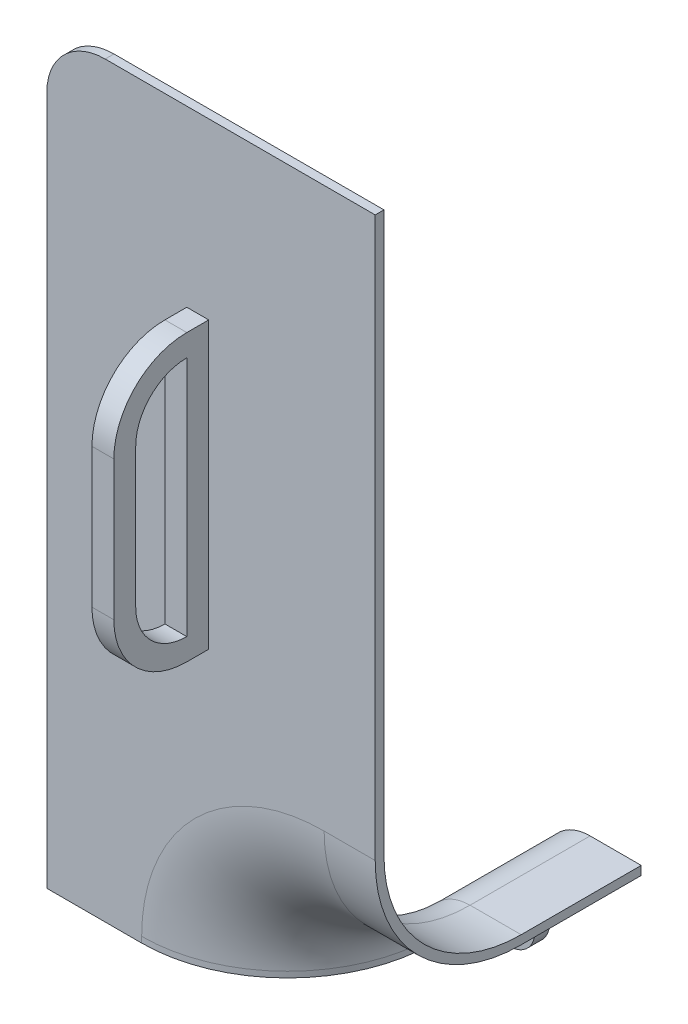
SolidWorks part; units mm, degrees
ref_plane "Front Plane" through (0, 0, 0) normal (0, 0, 1) x (1, 0, 0)
ref_plane "Top Plane" through (0, 0, 0) normal (0, 1, 0) x (1, 0, 0)
ref_plane "Right Plane" through (0, 0, 0) normal (1, 0, 0) x (0, 0, -1)
sketch "Sketch1" plane through (0, 0, 0) normal (0, 0, 1) x (1, 0, 0)
  line L0 (-72.7315, -496.2154) -> (-35.7315, -496.2154)
  line L2 (-35.7315, -496.2154) -> (-35.7315, -592.8312)
  line L3 (-47.7315, -598.6272) -> (-80.7315, -598.6272)
  line L4 (-80.7315, -598.6272) -> (-80.7315, -504.2154)
  line L5 (-50.7315, -599.6272) -> (-52.7315, -599.6272) construction
  line L7 (-0.7315, -587.8312) -> (-52.7315, -587.8312) construction
  line L10 (-35.7315, -592.8312) -> (-47.7315, -592.8312)
  line L11 (-47.7315, -598.6272) -> (-47.7315, -592.8312)
  line L16 (-52.7315, -714.7029) -> (-52.7315, -587.6272) construction
  arc A1 (-72.7315, -496.2154) -> (-80.7315, -504.2154) centre (-72.7315, -504.2154) ccw
  point P18 (0, 0)
  dimension "D1" = 1
  dimension "D2" = 45
  dimension "D3" = 5
  dimension "D4" = 5
extrude "Boss-Extrude1" add sketch "Sketch1" along normal offset from surface (36.45 mm away) 3
fillet "Fillet1" radius 5 1 edges at (-47.7315, -592.8312, 18.225)
fillet "Fillet2" radius 20 3 edges at (-47.7315, -598.2292, 36.45) (-39.2315, -592.8312, 36.45) (-46.267, -594.2956, 36.45)
shell "Shell2" thickness 1.2
sketch "Sketch3" plane through (0, 0, 8) normal (0, 0, 1) x (1, 0, 0)
  line L4 (-47.7315, -597.8312) -> (-47.7315, -600.2705)
  line L5 (-47.7315, -600.2705) -> (-43.7922, -600.2705)
  line L6 (-40.2922, -596.7705) -> (-40.2922, -592.8312)
  line L7 (-40.2922, -592.8312) -> (-42.7315, -592.8312)
  line L8 (-47.7315, -597.8312) -> (-47.7315, -600.2705)
  line L9 (-47.7315, -600.2705) -> (-43.7922, -600.2705)
  line L10 (-40.2922, -596.7705) -> (-40.2922, -592.8312)
  line L11 (-40.2922, -592.8312) -> (-42.7315, -592.8312)
  circle A1 centre (-43.7922, -596.7705) radius 1.5
  arc A2 (-42.7315, -592.8312) -> (-47.7315, -597.8312) centre (-42.7315, -597.8312) ccw
  arc A3 (-43.7922, -600.2705) -> (-40.2922, -596.7705) centre (-43.7922, -596.7705) ccw
  arc A4 (-42.7315, -592.8312) -> (-47.7315, -597.8312) centre (-42.7315, -597.8312) ccw
  arc A5 (-43.7922, -600.2705) -> (-40.2922, -596.7705) centre (-43.7922, -596.7705) ccw
  dimension "D1" = 0
extrude "Boss-Extrude2" add sketch "Sketch3" along normal blind 2
sketch "Sketch4" plane through (0, 0, 36.45) normal (0, 0, 1) x (1, 0, 0)
  line L1 (-61.5453, -520.0813) -> (-58.5453, -520.0813)
  line L2 (-61.5453, -520.0813) -> (-61.5453, -559.1646)
  line L3 (-61.5453, -559.1646) -> (-58.5453, -559.1646)
  line L4 (-58.5453, -520.0813) -> (-58.5453, -559.1646)
  dimension "D1" = 3
extrude "Boss-Extrude3" add sketch "Sketch4" along normal blind 13
fillet "Fillet3" radius 10 2 edges at (-60.0453, -559.1646, 49.45) (-60.0453, -520.0813, 49.45)
sketch "Sketch5" plane through (-58.5453, 0, 0) normal (1, 0, 0) x (0, 0, -1)
  line L4 (-49.45, -530.0813) -> (-49.45, -549.1646)
  line L5 (-39.45, -559.1646) -> (-36.45, -559.1646)
  line L6 (-36.45, -559.1646) -> (-36.45, -520.0813)
  line L7 (-36.45, -520.0813) -> (-39.45, -520.0813)
  line L8 (-49.45, -530.0813) -> (-49.45, -549.1646)
  line L9 (-39.45, -559.1646) -> (-36.45, -559.1646)
  line L10 (-36.45, -559.1646) -> (-36.45, -520.0813)
  line L11 (-36.45, -520.0813) -> (-39.45, -520.0813)
  line L16 (-46.45, -530.0813) -> (-46.45, -549.1646)
  line L17 (-39.45, -556.1646) -> (-39.45, -523.0813)
  line L18 (-46.45, -530.0813) -> (-46.45, -549.1646)
  line L19 (-39.45, -556.1646) -> (-39.45, -523.0813)
  arc A2 (-49.45, -549.1646) -> (-39.45, -559.1646) centre (-39.45, -549.1646) ccw
  arc A3 (-39.45, -520.0813) -> (-49.45, -530.0813) centre (-39.45, -530.0813) ccw
  arc A4 (-49.45, -549.1646) -> (-39.45, -559.1646) centre (-39.45, -549.1646) ccw
  arc A5 (-39.45, -520.0813) -> (-49.45, -530.0813) centre (-39.45, -530.0813) ccw
  arc A8 (-46.45, -549.1646) -> (-39.45, -556.1646) centre (-39.45, -549.1646) ccw
  arc A9 (-39.45, -523.0813) -> (-46.45, -530.0813) centre (-39.45, -530.0813) ccw
  arc A10 (-46.45, -549.1646) -> (-39.45, -556.1646) centre (-39.45, -549.1646) ccw
  arc A11 (-39.45, -523.0813) -> (-46.45, -530.0813) centre (-39.45, -530.0813) ccw
  dimension "D1" = 0
  dimension "D2" = 3
extrude "Cut-Extrude1" cut sketch "Sketch5" against normal blind 13 contours L19 A11 L18 A10
